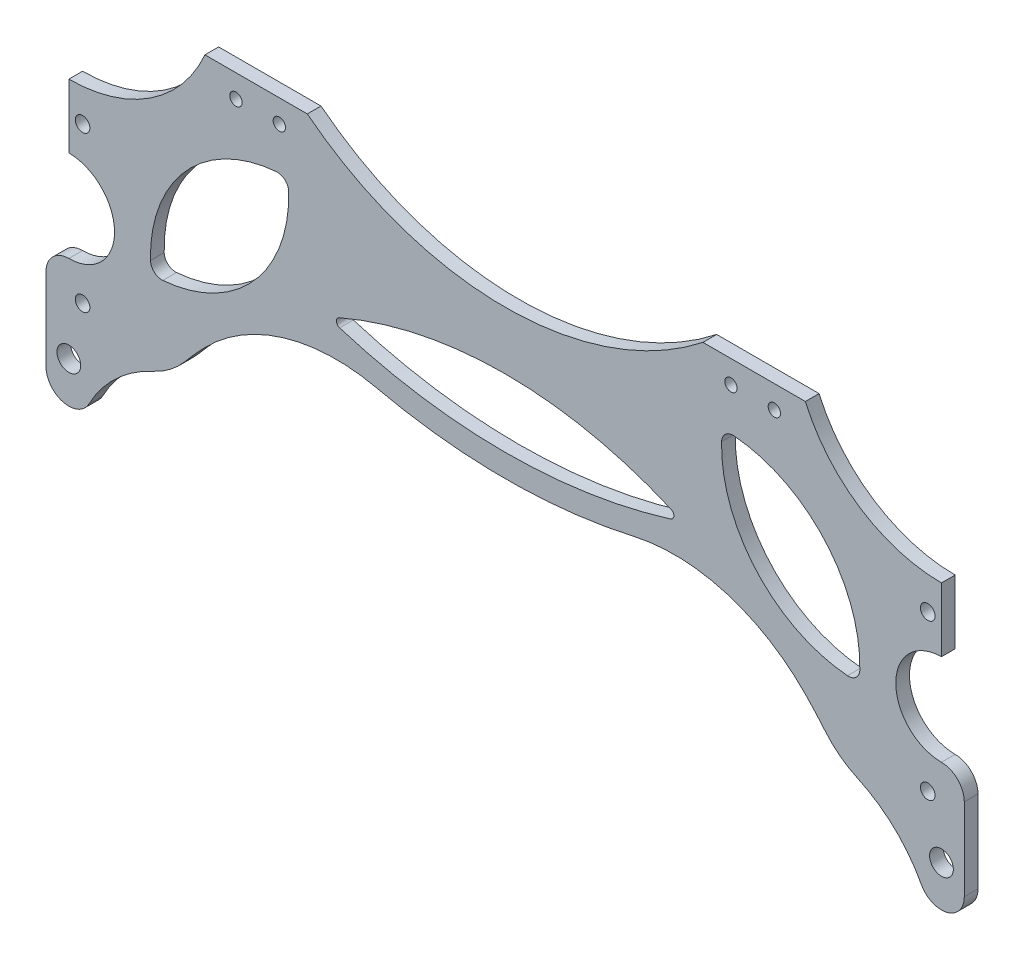
SolidWorks part; units mm, degrees
material "Thornel Mat VMA"
ref_plane "前视基准面" through (0, 0, 0) normal (0, 0, 1) x (1, 0, 0)
ref_plane "上视基准面" through (0, 0, 0) normal (0, 1, 0) x (1, 0, 0)
ref_plane "右视基准面" through (0, 0, 0) normal (1, 0, 0) x (0, 0, -1)
sketch "草图1" plane through (0, 0, 0) normal (0, 0, 1) x (1, 0, 0)
  line L0 (-95.5, -8.75) -> (95.5, -8.75) construction
  line L1 (-95.5, -33.75) -> (95.5, -33.75) construction
  line L2 (-95.5, -33.75) -> (-95.5, 33.75) construction
  line L3 (-95.5, 33.75) -> (95.5, 33.75) construction
  line L4 (95.5, -33.75) -> (95.5, 33.75) construction
  line L5 (-95.5, -33.75) -> (95.5, 33.75) construction
  line L6 (-95.5, 33.75) -> (95.5, -33.75) construction
  line L7 (-50, -8.75) -> (-50, -33.75) construction
  line L8 (50, -8.75) -> (50, -33.75) construction
  line L9 (-43.3013, 33.75) -> (-65.7133, 33.75)
  line L10 (-95.5, 14.25) -> (-95.5, 0.25)
  line L11 (-95.5, -19.75) -> (-95.5, -33.75)
  line L12 (-95.5, -33.75) -> (-75.5, -33.75)
  line L13 (0, 0) -> (0, -75.6259) construction
  line L14 (43.3013, 33.75) -> (65.7133, 33.75)
  line L15 (95.5, 14.25) -> (95.5, 0.25)
  line L16 (95.5, -19.75) -> (95.5, -33.75)
  line L17 (95.5, -33.75) -> (75.5, -33.75)
  circle A0 centre (0, -85.255) radius 91.3948 construction
  arc A1 (-75.5, -33.75) -> (75.5, -33.75) centre (0, -85.255) cw
  circle A2 centre (-95.5, -9.75) radius 10 construction
  circle A3 centre (-95.5, 46.75) radius 32.5 construction
  arc A4 (-95.5, -19.75) -> (-95.5, 0.25) centre (-95.5, -9.75) ccw
  arc A5 (-95.5, 14.25) -> (-65.7133, 33.75) centre (-95.5, 46.75) ccw
  arc A6 (95.5, -19.75) -> (95.5, 0.25) centre (95.5, -9.75) cw
  arc A7 (95.5, 14.25) -> (65.7133, 33.75) centre (95.5, 46.75) cw
  arc A8 (-43.3013, 33.75) -> (43.3013, 33.75) centre (0, 88.75) ccw
  point P0 (0, 0)
  point P12 (-75.5, -33.75)
  point P13 (75.5, -33.75)
  point P18 (-95.5, -9.75)
  point P21 (-95.5, 14.25)
  dimension "D8" = 24
  dimension "D9" = 20
  dimension "D11" = 65
  dimension "D12" = 140
  dimension "D1" = 67.5
  dimension "D2" = 191
  dimension "D3" = 25
  dimension "D4" = 50
  dimension "D5" = 50
  dimension "D6" = 20
  dimension "D7" = 20
  dimension "D10" = 48
  dimension "D13" = 55
extrude "凸台-拉伸1" add sketch "草图1" along normal blind 3 contours A8 L9 A5 L10 A4 L11 L12 A1 L17 L16 A6 L15 A7 L14
sketch "草图2" plane through (0, 0, 3) normal (0, 0, 1) x (1, 0, 0)
  line L0 (-43.3013, 33.75) -> (43.3013, 33.75) construction
  line L1 (0, 33.75) -> (0, -10.6023) construction
  line L2 (0, 33.75) -> (0, 113.75) construction
  circle A0 centre (0, 113.75) radius 125 construction
  arc A1 (-71.6448, 11.3194) -> (73.2747, 12.479) centre (0, 113.75) ccw
  dimension "D2" = 250
  dimension "D1" = 80
extrude "拉伸-薄壁1" add sketch "草图2" against normal up to surface (3 mm away) thin up to face at (0, 0.3934, 0) thin type mid plane wall 5
fillet "圆角1" radius 40 2 edges at (44.8284, -5.6094, 1.5) (-44.8284, -5.6094, 1.5)
sketch "草图3" plane through (0, 0, 3) normal (0, 0, 1) x (1, 0, 0)
  line L0 (-95.5, -33.75) -> (-29.5046, 39.5453) construction
  line L1 (-95.5, -33.75) -> (-75.5, -33.75) construction
  line L2 (0, 0) -> (0, 54.1854) construction
  line L3 (-62.5023, 2.8976) -> (-95.5, 32.6089) construction
  arc A0 (-77.4645, -13.7196) -> (-47.5401, 19.5149) centre (-77.3652, 16.2803) ccw
  arc A1 (-77.4645, -13.7196) -> (-47.5401, 19.5149) centre (-47.6394, -10.485) cw
  arc A2 (77.4645, -13.7196) -> (47.5401, 19.5149) centre (47.6394, -10.485) ccw
  arc A3 (77.4645, -13.7196) -> (47.5401, 19.5149) centre (77.3652, 16.2803) cw
  dimension "D2" = 60
  dimension "D1" = 20
  dimension "D3" = 98.6285
  dimension "D4" = 48
extrude "切除-拉伸1" cut sketch "草图3" against normal up to next
fillet "圆角2" radius 20 2 edges at (75.5, -33.75, 1.5) (-75.5, -33.75, 1.5)
sketch "草图4" plane through (0, 0, 3) normal (0, 0, 1) x (1, 0, 0)
  line L0 (-92.5, -33.75) -> (-92.5, -26.75) construction
  line L1 (-95.5, -33.75) -> (-85.4157, -33.75) construction
  line L2 (-95.5, -19.75) -> (-95.5, -33.75) construction
  line L3 (-92.5, -26.75) -> (-92.5, 7.25) construction
  line L5 (0, 0) -> (0, -52.8103) construction
  line L6 (92.5, -26.75) -> (92.5, 7.25) construction
  line L7 (92.5, -33.75) -> (92.5, -26.75) construction
  circle A0 centre (-92.5, -26.75) radius 1.6
  circle A1 centre (-92.5, 7.25) radius 1.6
  circle A2 centre (92.5, 7.25) radius 1.6
  circle A3 centre (92.5, -26.75) radius 1.6
  dimension "D3" = 3.2
  dimension "D5" = 3.2
  dimension "D1" = 3
  dimension "D2" = 7
  dimension "D4" = 34
extrude "切除-拉伸2" cut sketch "草图4" against normal up to next
sketch "草图5" plane through (0, 0, 3) normal (0, 0, 1) x (1, 0, 0)
  line L0 (-54.5073, 33.75) -> (-54.5073, 26.25) construction
  line L1 (-43.3013, 33.75) -> (-65.7133, 33.75) construction
  line L2 (0, 0) -> (0, 26.25) construction
  circle A0 centre (-54.5073, 26.25) radius 1.6
  circle A1 centre (54.5073, 26.25) radius 1.6
  dimension "D2" = 3.2
  dimension "D1" = 7.5
extrude "切除-拉伸3" [suppressed] cut sketch "草图5" against normal up to next
fillet "圆角3" radius 1 2 edges at (38.7228, -2.4688, 1.5) (-38.7228, -2.4688, 1.5)
sketch "草图6" plane through (0, 0, 3) normal (0, 0, 1) x (1, 0, 0)
  line L0 (-95.5, -24.75) -> (-95.5, -42.75) construction
  line L1 (-90.5, -24.75) -> (-90.5, -42.75)
  line L2 (-100.5, -24.75) -> (-100.5, -42.75)
  line L3 (0, 0) -> (0, -67.3999) construction
  line L4 (95.5, -24.75) -> (95.5, -42.75) construction
  line L5 (90.5, -24.75) -> (90.5, -42.75)
  line L6 (100.5, -24.75) -> (100.5, -42.75)
  arc A0 (-90.5, -24.75) -> (-100.5, -24.75) centre (-95.5, -24.75) ccw
  arc A1 (-100.5, -42.75) -> (-90.5, -42.75) centre (-95.5, -42.75) ccw
  circle A2 centre (-92.5, -26.75) radius 1.6
  circle A5 centre (92.5, -26.75) radius 1.6
  arc A6 (90.5, -24.75) -> (100.5, -24.75) centre (95.5, -24.75) cw
  arc A7 (100.5, -42.75) -> (90.5, -42.75) centre (95.5, -42.75) cw
  circle A8 centre (-95.5, -38.75) radius 2.6
  circle A9 centre (95.5, -38.75) radius 2.6
  point P2 (-95.5, -33.75)
  point P18 (95.5, -33.75)
  dimension "D1" = 3.2
  dimension "D2" = 5.2
  dimension "D3" = 5
extrude "凸台-拉伸2" add sketch "草图6" against normal up to surface (3 mm away) up to face at (94.1, -26.75, 0)
fillet "圆角4" radius 30 2 edges at (90.5, -33.75, 1.5) (-90.5, -33.75, 1.5)
fillet "圆角5" radius 2.5 4 edges at (-77.4645, -13.7196, 1.5) (-47.5401, 19.5149, 1.5) (77.4645, -13.7196, 1.5) (47.5401, 19.5149, 1.5)
sketch "草图8" plane through (0, 0, 0) normal (0, 0, -1) x (-1, 0, 0)
  line L0 (-43.3013, 33.75) -> (-65.7133, 33.75) construction
  line L1 (0, 0) -> (0, 27.8644) construction
  circle A0 centre (-58.9271, 28.75) radius 1.35
  circle A1 centre (-49.4271, 28.75) radius 1.35
  circle A2 centre (49.4271, 28.75) radius 1.35
  circle A3 centre (58.9271, 28.75) radius 1.35
  dimension "D1" = 2.7
  dimension "D2" = 2.7
  dimension "D3" = 9.5
  dimension "D4" = 5
extrude "切除-拉伸4" cut sketch "草图8" against normal blind 10
